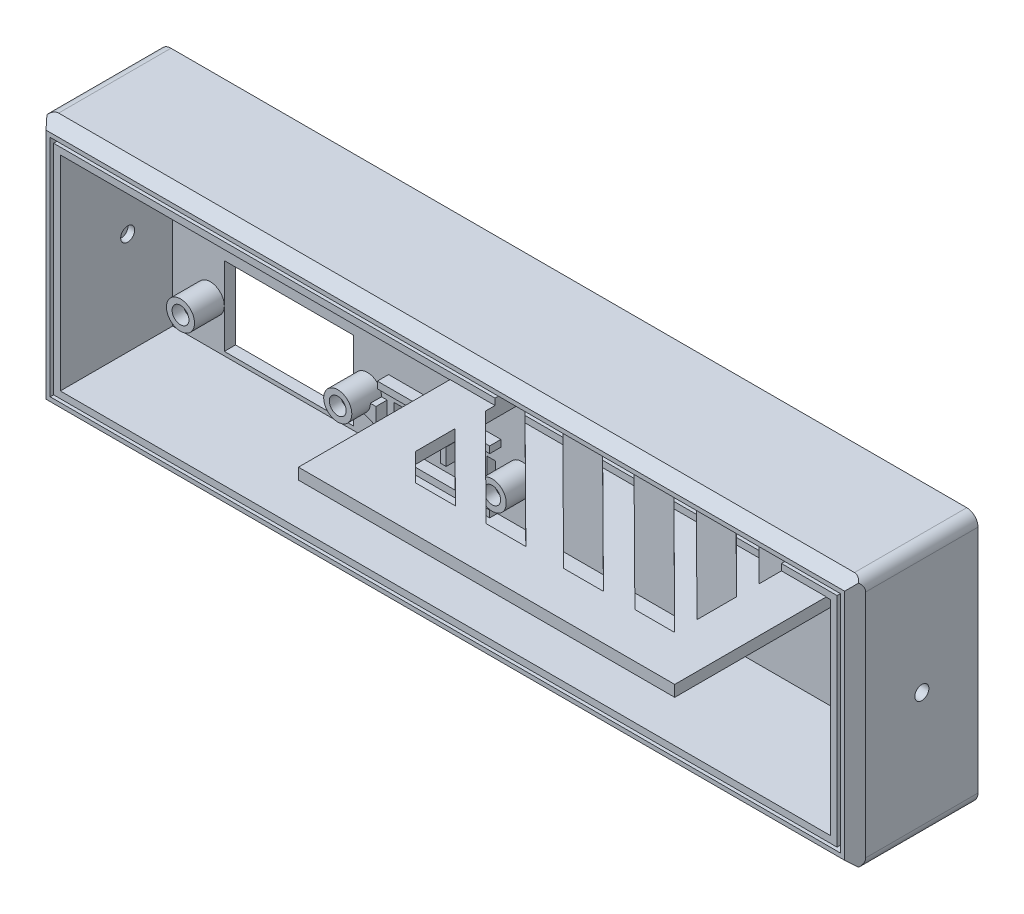
SolidWorks part; units mm, degrees
ref_plane "Front Plane" through (0, 0, 0) normal (0, 0, 1) x (1, 0, 0)
ref_plane "Top Plane" through (0, 0, 0) normal (0, 1, 0) x (1, 0, 0)
ref_plane "Right Plane" through (0, 0, 0) normal (1, 0, 0) x (0, 0, -1)
sketch "Sketch1" plane through (0, 0, 0) normal (0, 0, 1) x (1, 0, 0)
  line L1 (0, 0) -> (145.7, 0)
  line L2 (0, 0) -> (0, 45)
  line L3 (0, 45) -> (145.7, 45)
  line L4 (145.7, 0) -> (145.7, 45)
  dimension "D1" = 45
  dimension "D2" = 145.7
extrude "Boss-Extrude1" add sketch "Sketch1" along normal blind 2
sketch "Sketch2" plane through (0, 0, 0) normal (0, 0, -1) x (-1, 0, 0)
  line L0 (0, 45) -> (0, 0) construction
  line L1 (-30, 32.1) -> (-45, 32.1)
  line L2 (-30, 32.1) -> (-30, 39)
  line L3 (-30, 39) -> (-45, 39)
  line L4 (-45, 32.1) -> (-45, 39)
  line L5 (-50, 32.1) -> (-65, 32.1)
  line L6 (-50, 32.1) -> (-50, 39)
  line L7 (-50, 39) -> (-65, 39)
  line L8 (-65, 32.1) -> (-65, 39)
  line L9 (-145.7, 45) -> (0, 45) construction
  dimension "D1" = 6.9
  dimension "D2" = 15
  dimension "D3" = 5
  dimension "D4" = 30
  dimension "D5" = 6
extrude "usb" cut sketch "Sketch2" against normal up to next
sketch "Sketch3" plane through (0, 0, 2) normal (0, 0, 1) x (1, 0, 0)
  line L0 (65, 32.1) -> (65, 39) construction
  line L1 (45, 30.6) -> (30, 30.6)
  line L2 (45, 30.6) -> (45, 39)
  line L3 (45, 39) -> (30, 39)
  line L4 (30, 30.6) -> (30, 39)
  line L5 (50, 30.6) -> (65, 30.6)
  line L6 (50, 30.6) -> (50, 39)
  line L7 (50, 39) -> (65, 39)
  line L8 (65, 30.6) -> (65, 39)
  line L9 (30, 39) -> (30, 32.1) construction
  line L10 (45, 39) -> (30, 39) construction
  dimension "D1" = 8.4
extrude "usb_back" cut sketch "Sketch3" against normal blind 1
sketch "Sketch4" plane through (0, 0, 2) normal (0, 0, 1) x (1, 0, 0)
  line L0 (65, 39) -> (65, 38)
  line L5 (45, 39) -> (45, 38)
  line L10 (45, 30.6) -> (45, 39) construction
  line L15 (45, 38) -> (46.2, 38)
  line L24 (46.2, 38) -> (46.2, 41)
  line L25 (46.2, 41) -> (28.8, 41)
  line L26 (28.8, 41) -> (28.8, 38)
  line L27 (65, 30.6) -> (65, 39) construction
  line L28 (65, 38) -> (66.2, 38)
  line L29 (66.2, 38) -> (66.2, 41)
  line L30 (66.2, 41) -> (48.8, 41)
  line L31 (48.8, 41) -> (48.8, 38)
  line L32 (48.8, 38) -> (50, 38)
  line L33 (50, 39) -> (50, 30.6) construction
  line L34 (50, 38) -> (50, 39)
  line L35 (50, 39) -> (65, 39)
  line L44 (28.8, 38) -> (30, 38)
  line L45 (30, 39) -> (30, 30.6) construction
  line L46 (30, 38) -> (30, 39)
  line L47 (45, 39) -> (30, 39) construction
  line L48 (30, 39) -> (45, 39)
  dimension "D1" = 1.2
  dimension "D2" = 2
  dimension "D3" = 3
extrude "usb_back_support" add sketch "Sketch4" along normal blind 8
sketch "Sketch5" plane through (0, 0, 10) normal (0, 0, 1) x (1, 0, 0)
  line L1 (28.8, 38) -> (46.2, 38)
  line L2 (28.8, 38) -> (28.8, 41)
  line L3 (28.8, 41) -> (46.2, 41)
  line L4 (46.2, 38) -> (46.2, 41)
  line L5 (48.8, 38) -> (66.2, 38)
  line L6 (48.8, 38) -> (48.8, 41)
  line L7 (48.8, 41) -> (66.2, 41)
  line L8 (66.2, 38) -> (66.2, 41)
  line L10 (46.2, 41) -> (28.8, 41) construction
  line L11 (66.2, 41) -> (48.8, 41) construction
extrude "usb_back_support_2" add sketch "Sketch5" along normal blind 1.5
sketch "Sketch6" plane through (0, 0, 0) normal (0, 0, -1) x (-1, 0, 0)
  line L0 (0, 45) -> (0, 0) construction
  line L1 (-13.5, 5) -> (-36.5, 5)
  line L2 (-13.5, 5) -> (-13.5, 19)
  line L3 (-13.5, 19) -> (-36.5, 19)
  line L4 (-36.5, 5) -> (-36.5, 19)
  line L9 (0, 0) -> (-145.7, 0) construction
  dimension "D1" = 23
  dimension "D2" = 14
  dimension "D4" = 13.5
  dimension "D5" = 5
extrude "voltmeter_hole" cut sketch "Sketch6" against normal up to next
sketch "Sketch7" plane through (0, 0, 2) normal (0, 0, 1) x (1, 0, 0)
  line L0 (36.5, 19) -> (36.5, 5) construction
  line L1 (36.5, 5) -> (36.5, 19) construction
  line L3 (13.5, 19) -> (13.5, 5) construction
  circle A0 centre (66.5, 12) radius 2.5
  circle A1 centre (39, 12) radius 2.5
  circle A2 centre (11, 12) radius 2.5
  point P9 (36.5, 12)
  dimension "D1" = 2.5
  dimension "D2" = 5
  dimension "D3" = 2.5
  dimension "D4" = 30
extrude "voltmeter_plot" add sketch "Sketch7" along normal blind 5.3
sketch "Sketch10" plane through (0, 0, 7.3) normal (0, 0, 1) x (1, 0, 0)
  circle A0 centre (66.5, 12) radius 1.5
  circle A1 centre (39, 12) radius 1.5
  circle A2 centre (11, 12) radius 1.5
  circle A3 centre (11, 12) radius 2.5 construction
  circle A4 centre (39, 12) radius 2.5 construction
  circle A5 centre (66.5, 12) radius 2.5 construction
  dimension "D1" = 3
extrude "plot_hole" cut sketch "Sketch10" against normal blind 2
sketch "Sketch8" plane through (0, 0, 2) normal (0, 0, 1) x (1, 0, 0)
  line L0 (145.7, 45) -> (0, 45) construction
  line L1 (140.7, 38.75) -> (73.7, 38.75)
  line L2 (140.7, 38.75) -> (140.7, 40.75)
  line L3 (140.7, 40.75) -> (73.7, 40.75)
  line L4 (73.7, 38.75) -> (73.7, 40.75)
  line L5 (145.7, 0) -> (145.7, 45) construction
  dimension "D1" = 2
  dimension "D2" = 67
  dimension "D3" = 4.25
  dimension "D4" = 5
extrude "Boss-Extrude5" add sketch "Sketch8" along normal blind 47
sketch "Sketch9" plane through (0, 0, 0) normal (0, 0, -1) x (-1, 0, 0)
  line L0 (-30, 32.1) -> (-30, 39) construction
  line L1 (-20, 31) -> (-27, 31)
  line L2 (-20, 31) -> (-20, 40.5)
  line L3 (-20, 40.5) -> (-27, 40.5)
  line L4 (-27, 31) -> (-27, 40.5)
  line L5 (-8, 29.5) -> (-17, 29.5)
  line L6 (-8, 29.5) -> (-8, 40.5)
  line L7 (-8, 40.5) -> (-17, 40.5)
  line L8 (-17, 29.5) -> (-17, 40.5)
  line L9 (-145.7, 45) -> (0, 45) construction
  dimension "D1" = 7
  dimension "D2" = 9.5
  dimension "D3" = 3
  dimension "D4" = 4.5
  dimension "D5" = 9
  dimension "D6" = 11
  dimension "D7" = 3
extrude "dc" cut sketch "Sketch9" against normal up to next
sketch "Sketch11" plane through (0, 0, 0) normal (0, 0, -1) x (-1, 0, 0)
  line L0 (-36.5, 19) -> (-36.5, 5) construction
  line L1 (-43.75, 8.75) -> (-45.25, 8.75)
  line L2 (-43.75, 8.75) -> (-43.75, 12.25)
  line L3 (-43.75, 12.25) -> (-45.25, 12.25)
  line L4 (-45.25, 8.75) -> (-45.25, 12.25)
  line L5 (-47.75, 8.75) -> (-49.25, 8.75)
  line L6 (-47.75, 8.75) -> (-47.75, 12.25)
  line L7 (-47.75, 12.25) -> (-49.25, 12.25)
  line L8 (-49.25, 8.75) -> (-49.25, 12.25)
  line L9 (-56.25, 8.75) -> (-57.75, 8.75)
  line L10 (-56.25, 8.75) -> (-56.25, 12.25)
  line L11 (-56.25, 12.25) -> (-57.75, 12.25)
  line L12 (-57.75, 8.75) -> (-57.75, 12.25)
  line L13 (-60.25, 8.75) -> (-61.75, 8.75)
  line L14 (-60.25, 8.75) -> (-60.25, 12.25)
  line L15 (-60.25, 12.25) -> (-61.75, 12.25)
  line L16 (-61.75, 8.75) -> (-61.75, 12.25)
  circle A0 centre (-39, 12) radius 2.5 construction
  point P16 (-43.75, 10.5)
  dimension "D1" = 1.5
  dimension "D2" = 3.5
  dimension "D3" = 7.25
  dimension "D4" = 2.5
  dimension "D5" = 7
  dimension "D6" = 2.5
  dimension "D7" = 1.5
extrude "switch_hola" cut sketch "Sketch11" against normal up to next
sketch "Sketch12" plane through (0, 0, 2) normal (0, 0, 1) x (1, 0, 0)
  line L0 (62.75, 14.85) -> (42.75, 14.85)
  line L3 (65.25, 12) -> (63, 12)
  line L4 (63, 9) -> (63, 12)
  line L9 (55, 9) -> (54, 9)
  line L10 (55, 9) -> (55, 12)
  line L11 (55, 12) -> (54, 12)
  line L12 (54, 9) -> (54, 12)
  line L13 (51.5, 9) -> (50.5, 9)
  line L14 (51.5, 9) -> (51.5, 12)
  line L15 (51.5, 12) -> (50.5, 12)
  line L16 (50.5, 9) -> (50.5, 12)
  line L22 (42.5, 9) -> (42.5, 12)
  line L23 (42.5, 12) -> (40.25, 12)
  line L49 (62.75, 4.95) -> (42.75, 4.95)
  line L50 (62.75, 4.95) -> (62.75, 6.15)
  line L51 (62.75, 6.15) -> (42.75, 6.15)
  line L52 (42.75, 4.95) -> (42.75, 6.15)
  line L57 (62.75, 14.85) -> (62.75, 16.05)
  line L58 (62.75, 16.05) -> (42.75, 16.05)
  line L59 (42.75, 14.85) -> (42.75, 16.05)
  line L60 (61.75, 10.5) -> (43.75, 10.5) construction
  line L61 (61.75, 8.75) -> (61.75, 12.25) construction
  line L62 (43.75, 12.25) -> (43.75, 8.75) construction
  line L63 (44.5, 12.25) -> (44.5, 8.75) construction
  line L64 (45.25, 12.25) -> (43.75, 12.25) construction
  line L65 (43.75, 8.75) -> (45.25, 8.75) construction
  line L66 (48.5, 12.25) -> (48.5, 8.75) construction
  line L67 (49.25, 12.25) -> (47.75, 12.25) construction
  line L68 (47.75, 8.75) -> (49.25, 8.75) construction
  line L69 (57, 12.25) -> (57, 8.75) construction
  line L70 (57.75, 12.25) -> (56.25, 12.25) construction
  line L71 (56.25, 8.75) -> (57.75, 8.75) construction
  line L72 (61, 12.25) -> (61, 8.75) construction
  line L73 (61.75, 12.25) -> (60.25, 12.25) construction
  line L74 (60.25, 8.75) -> (61.75, 8.75) construction
  line L75 (40.25, 12) -> (40.25, 9.8349)
  line L76 (40.25, 9.8349) -> (42.5, 9)
  line L77 (65.25, 12) -> (65.25, 9.8349)
  line L78 (65.25, 9.8349) -> (63, 9)
  circle A0 centre (66.5, 12) radius 2.5 construction
  circle A1 centre (39, 12) radius 2.5 construction
  point P54 (42.5, 10.5)
  point P55 (55, 10.5)
  point P56 (50.5, 10.5)
  point P58 (52.75, 10.5)
  point P59 (52.75, 14.85)
  dimension "D3" = 8.7
  dimension "D8" = 2
  dimension "D1" = 20
  dimension "D2" = 1.2
  dimension "D4" = 2.25
  dimension "D5" = 2
  dimension "D6" = 3
  dimension "D7" = 2
  dimension "D10" = 1
  dimension "D9" = 2
  dimension "D11" = 1
extrude "switch_block" add sketch "Sketch12" along normal blind 2
sketch "Sketch13" plane through (0, 0, 2) normal (0, 0, 1) x (1, 0, 0)
  line L0 (62.75, 16.05) -> (42.75, 16.05) construction
  line L1 (47.9765, 23.05) -> (49.1765, 23.05)
  line L2 (47.9765, 23.05) -> (47.9765, 20.05)
  line L3 (47.9765, 20.05) -> (49.1765, 20.05)
  line L4 (49.1765, 23.05) -> (49.1765, 20.05)
  line L5 (59.1765, 23.05) -> (60.3765, 23.05)
  line L6 (59.1765, 23.05) -> (59.1765, 20.05)
  line L7 (59.1765, 20.05) -> (60.3765, 20.05)
  line L8 (60.3765, 23.05) -> (60.3765, 20.05)
  dimension "D1" = 1.2
  dimension "D2" = 3
  dimension "D3" = 4
  dimension "D4" = 10
extrude "support potar" [suppressed] add sketch "Sketch13" along normal blind 5
sketch "Sketch14" [suppressed] plane through (0, 0, 7) normal (0, 0, 1) x (1, 0, 0)
  line L1 (47.9765, 23.05) -> (60.3765, 23.05)
  line L2 (47.9765, 23.05) -> (47.9765, 20.05)
  line L3 (47.9765, 20.05) -> (60.3765, 20.05)
  line L4 (60.3765, 23.05) -> (60.3765, 20.05)
extrude "Boss-Extrude7" [suppressed] add sketch "Sketch14" along normal blind 1.2
sketch "Sketch15" plane through (0, 0, 2) normal (0, 0, 1) x (1, 0, 0)
  line L1 (46.8, 29.6) -> (54.3, 29.6)
  line L2 (46.8, 29.6) -> (46.8, 27.6)
  line L3 (46.8, 27.6) -> (54.3, 27.6)
  line L4 (54.3, 29.6) -> (54.3, 27.6)
  line L5 (50, 30.6) -> (65, 30.6) construction
  line L9 (50, 38) -> (50, 30.6) construction
  dimension "D1" = 2
  dimension "D2" = 7.5
  dimension "D3" = 1
  dimension "D4" = 3.2
extrude "trou roulette" cut sketch "Sketch15" against normal up to next
sketch "Sketch16" plane through (0, 0, 2) normal (0, 0, 1) x (1, 0, 0)
  line L0 (54.3, 29.6) -> (46.8, 29.6) construction
  line L1 (54.8, 29.6) -> (46.3, 29.6)
  line L2 (54.8, 29.6) -> (54.8, 27.6)
  line L3 (54.8, 27.6) -> (46.3, 27.6)
  line L4 (46.3, 29.6) -> (46.3, 27.6)
  line L5 (46.8, 27.6) -> (54.3, 27.6) construction
  point P8 (50.55, 29.6)
  point P9 (50.55, 29.6)
  dimension "D1" = 8.5
extrude "Cut-Extrude2" cut sketch "Sketch16" against normal blind 0.5
sketch "Sketch17" plane through (0, 0, 2) normal (0, 0, 1) x (1, 0, 0)
  line L1 (0, 45) -> (145.7, 45)
  line L2 (0, 45) -> (0, 0)
  line L3 (0, 0) -> (145.7, 0)
  line L4 (145.7, 45) -> (145.7, 0)
  line L5 (143.2, 2.5) -> (2.5, 2.5)
  line L6 (143.2, 2.5) -> (143.2, 42.5)
  line L7 (143.2, 42.5) -> (2.5, 42.5)
  line L8 (2.5, 2.5) -> (2.5, 42.5)
  line L9 (3.1, 41.9) -> (142.6, 41.9)
  line L10 (3.1, 41.9) -> (3.1, 3.1)
  line L11 (3.1, 3.1) -> (142.6, 3.1)
  line L12 (142.6, 41.9) -> (142.6, 3.1)
  line L13 (4.3, 40.7) -> (141.4, 40.7)
  line L14 (4.3, 40.7) -> (4.3, 4.3)
  line L15 (4.3, 4.3) -> (141.4, 4.3)
  line L16 (141.4, 40.7) -> (141.4, 4.3)
  point P18 (143.2, 22.5)
  point P19 (145.7, 22.5)
  point P20 (142.6, 22.5)
  point P21 (141.4, 22.5)
  point P22 (72.85, 42.5)
  point P23 (72.85, 45)
  point P24 (72.85, 41.9)
  point P25 (72.85, 40.7)
  dimension "D1" = 0.6
  dimension "D2" = 0.6
  dimension "D3" = 2.5
  dimension "D4" = 2.5
  dimension "D5" = 1.2
  dimension "D6" = 1.2
extrude "bord " add sketch "Sketch17" along normal blind 20 contours L4 L1 L2 L3 L5 L8 L7 L6 | L12 L9 L10 L11 L13 L16 L15 L14
fillet "Fillet1" radius 2 4 edges at (0, 0, 11) (145.7, 0, 11) (145.7, 45, 11) (0, 45, 11)
sketch "Sketch18" plane through (0, 38.75, 0) normal (0, -1, 0) x (1, 0, 0)
  line L0 (81.7, 36.1785) -> (86.5549, 41)
  line L1 (86.5549, 41) -> (93.6505, 41)
  line L2 (93.6505, 41) -> (81.7, 29.1318)
  line L3 (81.7, 29.1318) -> (81.7, 36.1785)
  line L4 (81.7, 23.7224) -> (99.0973, 41)
  line L5 (99.0973, 41) -> (106.1929, 41)
  line L6 (106.1929, 41) -> (81.7, 16.6757)
  line L7 (81.7, 16.6757) -> (81.7, 23.7224)
  line L8 (81.7, 10) -> (112.9148, 41)
  line L9 (112.9148, 41) -> (120.0104, 41)
  line L10 (120.0104, 41) -> (88.7956, 10)
  line L11 (88.7956, 10) -> (81.7, 10)
  line L12 (140.7, 49) -> (140.7, 2) construction
  line L13 (94.3896, 10) -> (125.6044, 41)
  line L14 (125.6044, 41) -> (132.7, 41)
  line L15 (132.7, 41) -> (101.4852, 10)
  line L16 (101.4852, 10) -> (94.3896, 10)
  line L17 (105.4795, 10) -> (132.7, 37.0331)
  line L18 (132.7, 37.0331) -> (132.7, 29.9864)
  line L19 (132.7, 29.9864) -> (112.5751, 10)
  line L20 (112.5751, 10) -> (105.4795, 10)
  line L21 (116.6029, 10) -> (132.7, 25.9864)
  line L22 (132.7, 25.9864) -> (132.7, 18.9396)
  line L23 (132.7, 18.9396) -> (123.6985, 10)
  line L24 (123.6985, 10) -> (116.6029, 10)
  line L25 (73.7, 49) -> (140.7, 49) construction
  line L26 (73.7, 2) -> (140.7, 2) construction
  line L27 (73.7, 49) -> (73.7, 2) construction
  dimension "D1" = 5
  dimension "D2" = 8
  dimension "D3" = 8
  dimension "D4" = 8
  dimension "D5" = 8
  dimension "D6" = 4
extrude "Cut-Extrude3" cut sketch "Sketch18" against normal up to surface (3.15 mm away) up to face at (72.85, 41.9, 12)
sketch "Sketch19" plane through (145.7, 0, 0) normal (1, 0, 0) x (0, 0, -1)
  line L0 (-22, 43.25) -> (-20, 45)
  line L1 (-22, 43) -> (-22, 2) construction
  line L2 (-20, 45) -> (-22, 45)
  line L3 (-22, 45) -> (-22, 43.25)
  line L4 (-22, 45) -> (0, 45) construction
  line L5 (-22, 1.75) -> (-20, 0)
  line L6 (0, 0) -> (-22, 0) construction
  line L7 (-20, 0) -> (-22, 0)
  line L8 (-22, 0) -> (-22, 1.75)
  dimension "D1" = 2
  dimension "D2" = 1.75
extrude "Cut-Extrude4" cut sketch "Sketch19" against normal up to surface (145.7 mm away) up to face at (0, 22.5, 11)
sketch "Sketch20" plane through (0, 0, 0) normal (0, -1, 0) x (-1, 0, 0)
  line L0 (-143.95, -22) -> (-145.7, -20)
  line L1 (-0.0157, -22) -> (-145.6843, -22) construction
  line L3 (-145.7, -20) -> (-145.7, -22)
  line L4 (-145.7, -22) -> (-143.95, -22)
  line L5 (-1.75, -22) -> (0, -20)
  line L7 (0, -20) -> (0, -22)
  line L8 (0, -22) -> (-1.75, -22)
  line L9 (-145.7, 0) -> (-145.7, -22) construction
  line L10 (0, -22) -> (0, 0) construction
  dimension "D1" = 1.75
  dimension "D2" = 2
extrude "Cut-Extrude5" cut sketch "Sketch20" against normal up to surface (45 mm away) up to face at (72.85, 45, 10)
sketch "Sketch21" plane through (0, 0, 0) normal (-1, 0, 0) x (0, 0, 1)
  line L0 (20, 43) -> (20, 2) construction
  line L1 (0, 2) -> (20, 2) construction
  circle A0 centre (10, 22.5) radius 1.25
  point P5 (20, 22.5)
  point P9 (10, 2)
  dimension "D1" = 2.5
extrude "Cut-Extrude6" cut sketch "Sketch21" against normal up to surface (145.7 mm away) up to face at (145.7, 22.5, 10)
